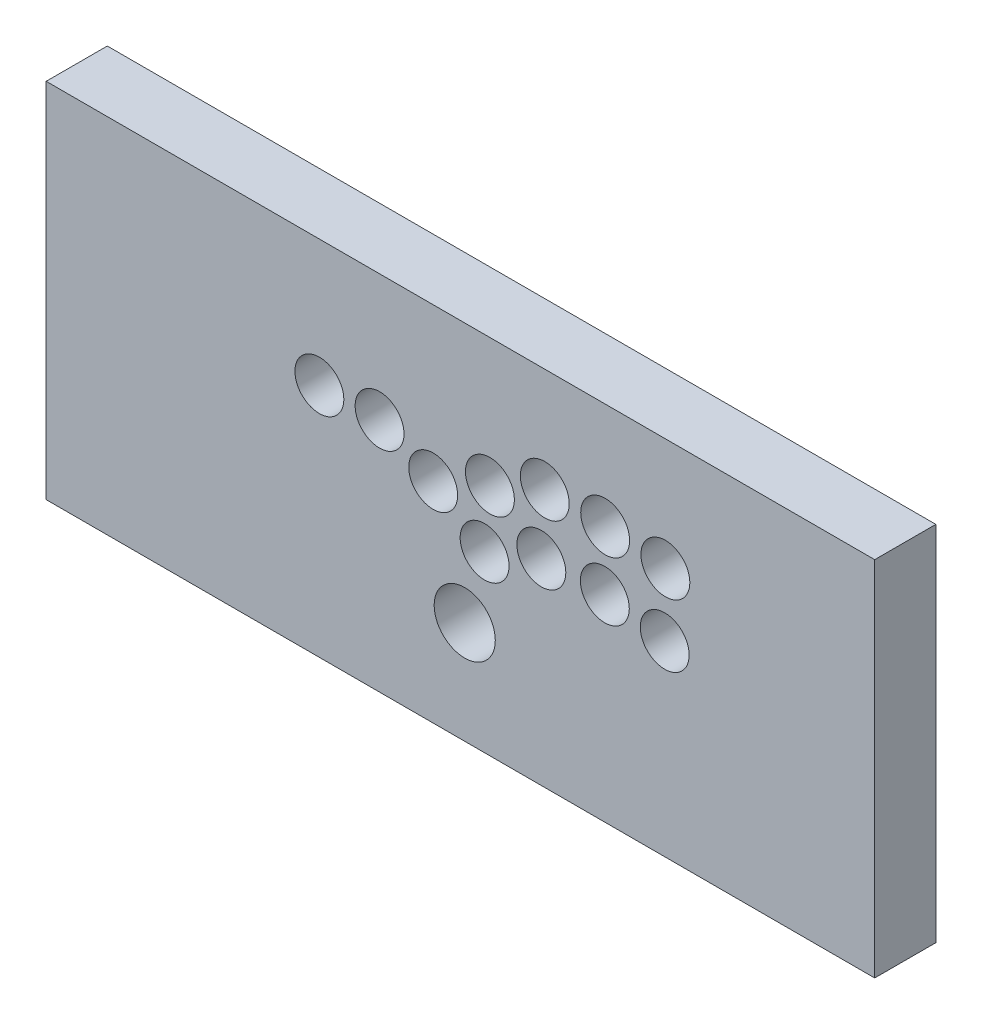
SolidWorks part; units mm, degrees
ref_plane "Plan de face" through (0, 0, 0) normal (0, 0, 1) x (1, 0, 0)
ref_plane "Plan de dessus" through (0, 0, 0) normal (0, 1, 0) x (1, 0, 0)
ref_plane "Plan de droite" through (0, 0, 0) normal (1, 0, 0) x (0, 0, -1)
sketch "Model" plane through (0, 0, 0) normal (0, 0, 1) x (1, 0, 0)
  line L0 (0, 0) -> (406.6, 0)
  line L1 (406.6, 0) -> (406.6, 177.8)
  line L2 (406.6, 177.8) -> (0, 177.8)
  line L3 (0, 177.8) -> (0, 0)
  line L4 (243.01, 96.4473) -> (243.01, 105.4473)
  line L5 (243.01, 96.4473) -> (252.01, 96.4473)
  line L6 (243.01, 96.4473) -> (243.01, 87.4473)
  line L7 (243.01, 96.4473) -> (234.01, 96.4473)
  line L8 (274.1606, 96.7225) -> (274.1606, 105.7225)
  line L9 (274.1606, 96.7225) -> (283.1606, 96.7225)
  line L10 (274.1606, 96.7225) -> (274.1606, 87.7225)
  line L11 (274.1606, 96.7225) -> (265.1606, 96.7225)
  line L12 (274.3304, 125.7435) -> (274.3304, 134.7435)
  line L13 (274.3304, 125.7435) -> (283.3304, 125.7435)
  line L14 (274.3304, 125.7435) -> (274.3304, 116.7435)
  line L15 (274.3304, 125.7435) -> (265.3304, 125.7435)
  line L16 (244.6882, 126.5512) -> (244.6882, 135.5512)
  line L17 (244.6882, 126.5512) -> (253.6882, 126.5512)
  line L18 (244.6882, 126.5512) -> (244.6882, 117.5512)
  line L19 (244.6882, 126.5512) -> (235.6882, 126.5512)
  line L20 (217.7703, 114.8294) -> (217.7703, 123.8294)
  line L21 (217.7703, 114.8294) -> (226.7703, 114.8294)
  line L22 (217.7703, 114.8294) -> (217.7703, 105.8294)
  line L23 (217.7703, 114.8294) -> (208.7703, 114.8294)
  line L24 (189.9314, 102.813) -> (189.9314, 111.813)
  line L25 (189.9314, 102.813) -> (198.9314, 102.813)
  line L26 (189.9314, 102.813) -> (189.9314, 93.813)
  line L27 (189.9314, 102.813) -> (180.9314, 102.813)
  line L28 (215.1488, 85.431) -> (215.1488, 94.431)
  line L29 (215.1488, 85.431) -> (224.1488, 85.431)
  line L30 (215.1488, 85.431) -> (215.1488, 76.431)
  line L31 (215.1488, 85.431) -> (206.1488, 85.431)
  line L32 (303.5476, 91.7017) -> (303.5476, 100.7017)
  line L33 (303.5476, 91.7017) -> (312.5476, 91.7017)
  line L34 (303.5476, 91.7017) -> (303.5476, 82.7017)
  line L35 (303.5476, 91.7017) -> (294.5476, 91.7017)
  line L36 (303.8769, 122.6561) -> (303.8769, 131.6561)
  line L37 (303.8769, 122.6561) -> (312.8769, 122.6561)
  line L38 (303.8769, 122.6561) -> (303.8769, 113.6561)
  line L39 (303.8769, 122.6561) -> (294.8769, 122.6561)
  line L40 (163.6193, 115.7093) -> (163.6193, 124.7093)
  line L41 (163.6193, 115.7093) -> (172.6193, 115.7093)
  line L42 (163.6193, 115.7093) -> (163.6193, 106.7093)
  line L43 (163.6193, 115.7093) -> (154.6193, 115.7093)
  line L44 (134.0793, 115.6205) -> (134.0793, 124.6205)
  line L45 (134.0793, 115.6205) -> (143.0793, 115.6205)
  line L46 (134.0793, 115.6205) -> (134.0793, 106.6205)
  line L47 (134.0793, 115.6205) -> (125.0793, 115.6205)
  line L48 (205.4066, 50.3604) -> (205.4066, 59.3604)
  line L49 (205.4066, 50.3604) -> (214.4066, 50.3604)
  line L50 (205.4066, 50.3604) -> (205.4066, 41.3604)
  line L51 (205.4066, 50.3604) -> (196.4066, 50.3604)
  line L53 (0, 177.8) -> (406.6, 177.8)
  line L54 (0, 177.8) -> (0, 0)
  line L55 (0, 0) -> (406.6, 0)
  line L56 (406.6, 177.8) -> (406.6, 0)
  line L57 (0, 0) -> (406.6, 0)
  line L58 (0, 0) -> (0, 177.8)
  line L59 (0, 177.8) -> (406.6, 177.8)
  line L60 (406.6, 0) -> (406.6, 177.8)
  circle A0 centre (215.1488, 85.431) radius 12
  circle A1 centre (243.01, 96.4473) radius 12
  circle A2 centre (303.5476, 91.7017) radius 12
  circle A3 centre (303.8769, 122.6561) radius 12
  circle A4 centre (274.3304, 125.7435) radius 12
  circle A5 centre (244.6882, 126.5512) radius 12
  circle A6 centre (217.7703, 114.8294) radius 12
  circle A7 centre (189.9314, 102.813) radius 12
  circle A8 centre (163.6193, 115.7093) radius 12
  circle A9 centre (134.0793, 115.6205) radius 12
  circle A10 centre (274.1606, 96.7225) radius 12
  circle A11 centre (205.4066, 50.3604) radius 15
  circle A12 centre (134.0793, 115.6205) radius 12
  circle A13 centre (163.6193, 115.7093) radius 12
  circle A14 centre (189.9314, 102.813) radius 12
  circle A15 centre (215.1488, 85.431) radius 12
  circle A16 centre (205.4066, 50.3604) radius 15
  circle A17 centre (217.7703, 114.8294) radius 12
  circle A18 centre (243.01, 96.4473) radius 12
  circle A19 centre (244.6882, 126.5512) radius 12
  circle A20 centre (274.3304, 125.7435) radius 12
  circle A21 centre (303.8769, 122.6561) radius 12
  circle A22 centre (303.5476, 91.7017) radius 12
  circle A23 centre (274.1606, 96.7225) radius 12
  point P88 (0, 0)
sketch "Esquisse2" plane through (0, 0, 0) normal (0, 0, 1) x (1, 0, 0)
  line L1 (0, 177.8) -> (406.6, 177.8)
  line L2 (0, 177.8) -> (0, 0)
  line L3 (0, 0) -> (406.6, 0)
  line L4 (406.6, 177.8) -> (406.6, 0)
  circle A0 centre (134.0793, 115.6205) radius 12
  circle A1 centre (163.6193, 115.7093) radius 12
  circle A2 centre (189.9314, 102.813) radius 12
  circle A3 centre (215.1488, 85.431) radius 12
  circle A4 centre (205.4066, 50.3604) radius 15
  circle A5 centre (217.7703, 114.8294) radius 12
  circle A6 centre (244.6882, 126.5512) radius 12
  circle A7 centre (274.3304, 125.7435) radius 12
  circle A8 centre (303.8769, 122.6561) radius 12
  circle A9 centre (303.5476, 91.7017) radius 12
  circle A10 centre (274.1606, 96.7225) radius 12
  circle A11 centre (243.01, 96.4473) radius 12
extrude "Boss.-Extru.3" add sketch "Esquisse2" along normal blind 30
sketch "Esquisse4" plane through (0, 0, 0) normal (0, 0, -1) x (-1, 0, 0)
  line L1 (-406.6, 177.8) -> (0, 177.8)
  line L2 (-406.6, 177.8) -> (-406.6, 0)
  line L3 (-406.6, 0) -> (0, 0)
  line L4 (0, 177.8) -> (0, 0)
extrude "Boss.-Extru.4" add sketch "Esquisse4" against normal blind 4
